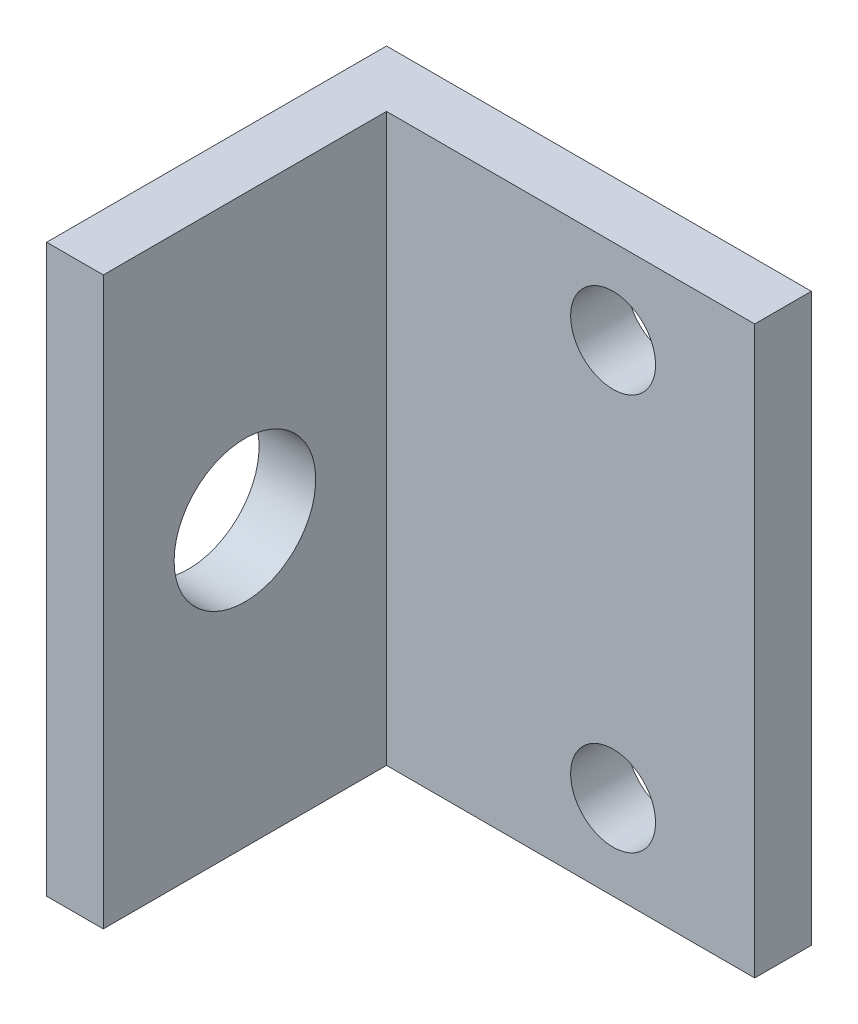
SolidWorks part; units mm, degrees
material "6061 Alloy"
ref_plane "Front Plane" through (0, 0, 0) normal (0, 0, 1) x (1, 0, 0)
ref_plane "Top Plane" through (0, 0, 0) normal (0, 1, 0) x (1, 0, 0)
ref_plane "Right Plane" through (0, 0, 0) normal (1, 0, 0) x (0, 0, -1)
sketch "Sketch1" plane through (0, 0, 0) normal (0, 1, 0) x (1, 0, 0)
  line L0 (0, 0) -> (0, 12)
  line L1 (0, -5.5) -> (0, 5.5) construction
  line L2 (0, 12) -> (15, 12)
  dimension "D1" = 12
  dimension "D2" = 15
extrude "Extrude-Thin1" add sketch "Sketch1" along normal blind 20 thin
sketch "Sketch2" plane through (0, 0, 0) normal (-1, 0, 0) x (0, 0, 1)
  line L0 (0, -8.25) -> (0, 8.25) construction
  line L1 (0, 20) -> (-12, 20) construction
  circle A0 centre (-5, 10) radius 2.5
  dimension "D1" = 5
  dimension "D2" = 5
  dimension "D3" = 10
extrude "Cut-Extrude1" cut sketch "Sketch2" against normal blind 10
sketch "Sketch3" plane through (0, 0, -12) normal (0, 0, -1) x (-1, 0, 0)
  line L0 (0, 20) -> (-15, 20) construction
  line L1 (-15, 20) -> (-15, 0) construction
  line L2 (5.5, 0) -> (-5.5, 0) construction
  circle A0 centre (-10, 17) radius 1.5
  circle A1 centre (-10, 3) radius 1.5
  dimension "D1" = 3
  dimension "D2" = 3
  dimension "D3" = 5
  dimension "D5" = 3
extrude "Cut-Extrude2" cut sketch "Sketch3" against normal blind 10
